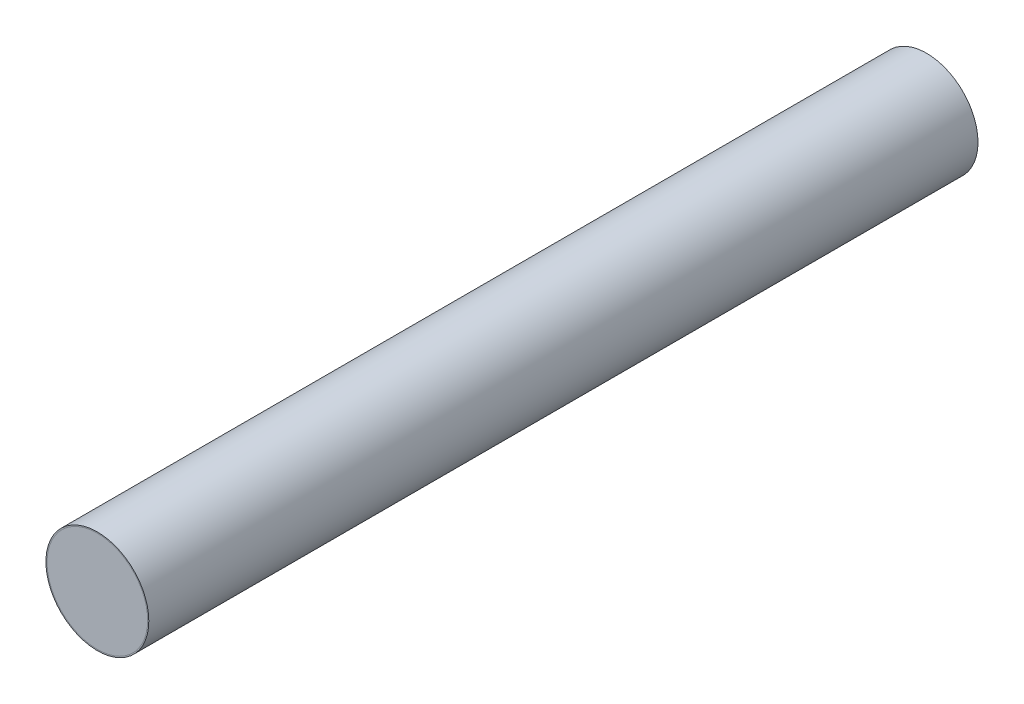
SolidWorks part; units mm, degrees
other "8627X"
other "03170L"
material "APCP"
ref_plane "Front Plane" through (0, 0, 0) normal (0, 0, 1) x (1, 0, 0)
ref_plane "Top Plane" through (0, 0, 0) normal (0, 1, 0) x (1, 0, 0)
ref_plane "Right Plane" through (0, 0, 0) normal (1, 0, 0) x (0, 0, -1)
sketch "Sketch1" plane through (0, 0, 0) normal (0, 0, 1) x (1, 0, 0)
  circle A0 centre (0, 0) radius 16.5481
  circle A1 centre (0, 0) radius 16.1798
  dimension "D1" = 33.0962
  dimension "D2" = 32.3596
extrude "Boss-Extrude1" add sketch "Sketch1" along normal blind 266.7
sketch "Sketch2" plane through (0, 0, 0) normal (0, 0, 1) x (1, 0, 0)
  circle A0 centre (0, 0) radius 16.1798
  circle A1 centre (0, 0) radius 16.1798 construction
extrude "Boss-Extrude2" add sketch "Sketch2" along normal up to surface (266.7 mm away) separate body up to face at (16.5481, 0, 266.7)
sketch "Sketch3" [suppressed] plane through (0, 0, 72.5424) normal (0, 0, 1) x (1, 0, 0)
  point P0 (0, 0)
hole_wizard "7/16 (0.438) Diameter Hole1" [suppressed] positions "Sketch3" profile "Sketch4" hole size "7/16" standard "ANSI Inch"
sketch "Sketch4" plane through (0, 0, 72.5424) normal (1, 0, 0) x (0, -1, 0)
  line L0 (0, 0) -> (0, 72.5424)
  line L1 (0, 72.5424) -> (5.5626, 72.5424)
  line L2 (5.5626, 72.5424) -> (5.5626, 0)
  line L5 (5.5626, 0) -> (0, 0)
  line L11 (0, -6.35) -> (0, 107.95) construction
  dimension "Thru Hole Dia." = 11.1252
  dimension "Thru Hole Depth" = 72.5424
